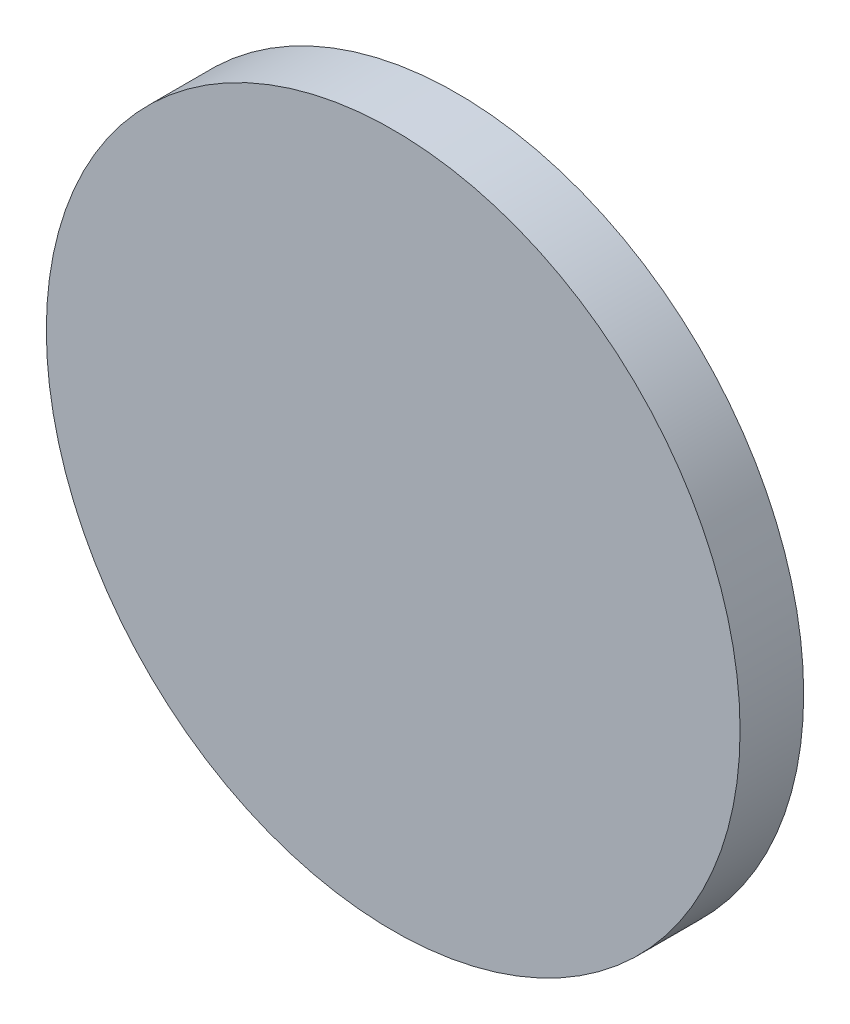
SolidWorks part; units mm, degrees
ref_plane "Plan de face" through (0, 0, 0) normal (0, 0, 1) x (1, 0, 0)
ref_plane "Plan de dessus" through (0, 0, 0) normal (0, 1, 0) x (1, 0, 0)
ref_plane "Plan de droite" through (0, 0, 0) normal (1, 0, 0) x (0, 0, -1)
sketch "Esquisse1" plane through (0, 0, 0) normal (0, 0, 1) x (1, 0, 0)
  circle A0 centre (0, 0) radius 30
  dimension "D1" = 60
extrude "Boss.-Extru.1" add sketch "Esquisse1" along normal blind 5.5
sketch "Esquisse2" plane through (0, 0, 0) normal (0, 0, -1) x (-1, 0, 0)
  circle A0 centre (0, 0) radius 2.5
  dimension "D1" = 5
extrude "Enlèv. mat.-Extru.1" cut sketch "Esquisse2" against normal blind 2
